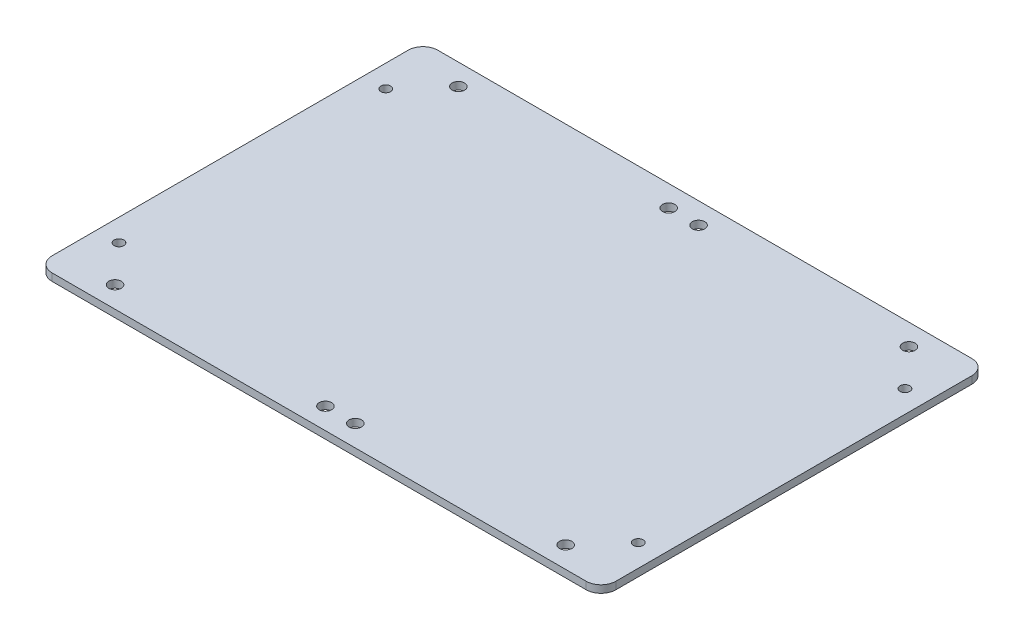
SolidWorks part; units mm, degrees
ref_plane "Front Plane" through (0, 0, 0) normal (0, 0, 1) x (1, 0, 0)
ref_plane "Top Plane" through (0, 0, 0) normal (0, 1, 0) x (1, 0, 0)
ref_plane "Right Plane" through (0, 0, 0) normal (1, 0, 0) x (0, 0, -1)
sketch "Sketch1" plane through (0, 0, 0) normal (0, 1, 0) x (1, 0, 0)
  line L0 (0, 165.1) -> (406.4, 165.1) construction
  line L1 (0, 0) -> (406.4, 0)
  line L3 (0, 330.2) -> (406.4, 330.2)
  line L5 (203.2, 165.1) -> (203.2, 330.2) construction
  line L6 (0, 330.2) -> (-38.1, 330.2)
  line L7 (-38.1, 330.2) -> (-38.1, 0)
  line L8 (-38.1, 0) -> (0, 0)
  line L9 (444.5, 0) -> (406.4, 0)
  line L10 (406.4, 330.2) -> (444.5, 330.2)
  line L11 (444.5, 330.2) -> (444.5, 0)
  line L12 (-19.05, 330.2) -> (-19.05, 0) construction
  line L13 (425.45, 330.2) -> (425.45, 0) construction
  circle A0 centre (10.3249, 312.039) radius 5.334
  circle A1 centre (10.3249, 18.161) radius 5.334
  circle A2 centre (190.4109, 312.039) radius 5.334
  circle A3 centre (190.4109, 18.161) radius 5.334
  circle A4 centre (215.9891, 18.161) radius 5.334
  circle A5 centre (396.0751, 18.161) radius 5.334
  circle A6 centre (215.9891, 312.039) radius 5.334
  circle A7 centre (396.0751, 312.039) radius 5.334
  circle A8 centre (-19.05, 279.273) radius 4.191
  circle A9 centre (-19.05, 50.927) radius 4.191
  circle A10 centre (425.45, 50.927) radius 4.191
  circle A11 centre (425.45, 279.273) radius 4.191
  dimension "D3" = 10.668
  dimension "D6" = 10.668
  dimension "D7" = 10.668
  dimension "D11" = 8.382
  dimension "D1" = 330.2
  dimension "D2" = 406.4
  dimension "D4" = 293.878
  dimension "D5" = 146.939
  dimension "D8" = 180.086
  dimension "D9" = 38.1
  dimension "D10" = 114.173
extrude "Boss-Extrude1" add sketch "Sketch1" along normal blind 6.35
fillet "Fillet1" radius 12.7 4 edges at (444.5, 3.175, 0) (-38.1, 3.175, 0) (-38.1, 3.175, -330.2) (444.5, 3.175, -330.2)
